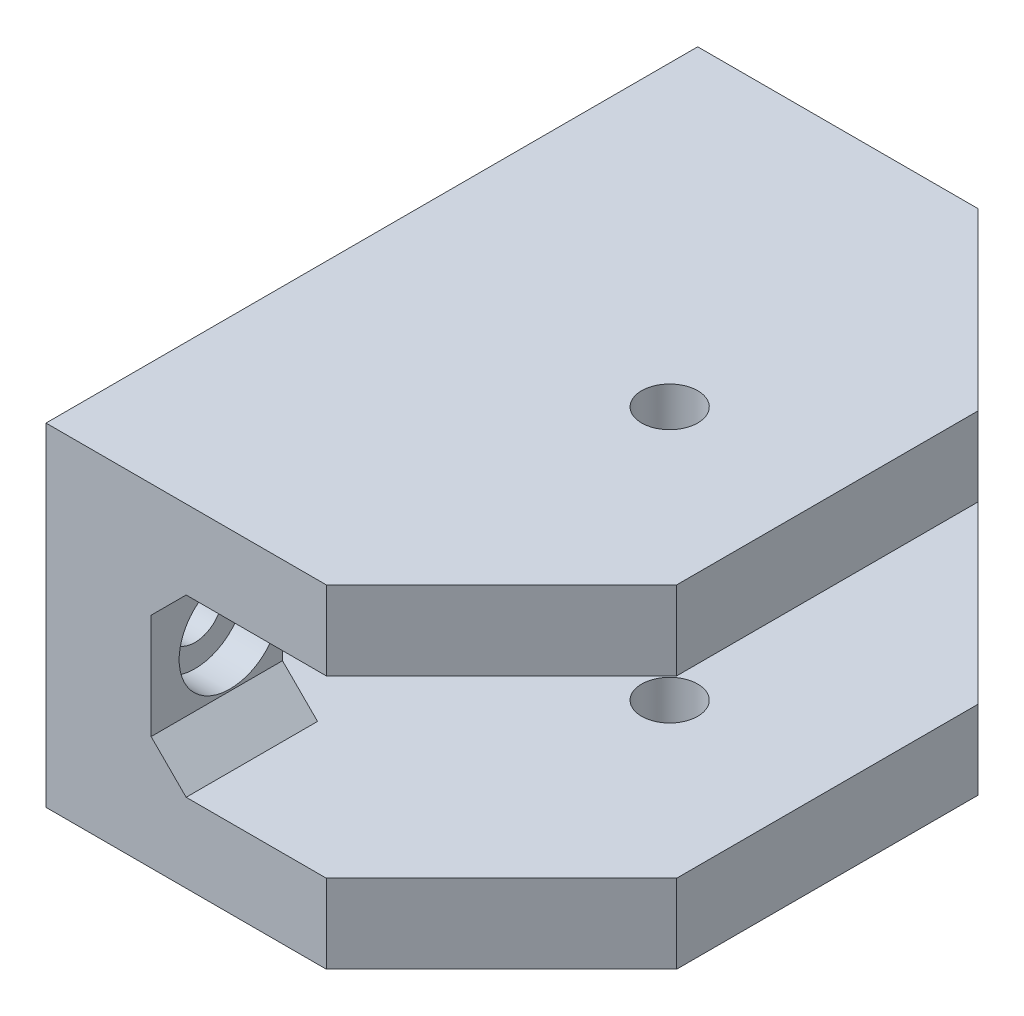
SolidWorks part; units mm, degrees
ref_plane "Front Plane" through (0, 0, 0) normal (0, 0, 1) x (1, 0, 0)
ref_plane "Top Plane" through (0, 0, 0) normal (0, 1, 0) x (1, 0, 0)
ref_plane "Right Plane" through (0, 0, 0) normal (1, 0, 0) x (0, 0, -1)
sketch "Sketch1" plane through (0, 0, 0) normal (0, 1, 0) x (1, 0, 0)
  line L1 (38.6007, -34.5861) -> (64.6007, -34.5861)
  line L2 (38.6007, -34.5861) -> (38.6007, 2.6139)
  line L3 (38.6007, 2.6139) -> (64.6007, 2.6139)
  line L4 (64.6007, -34.5861) -> (64.6007, 2.6139)
  dimension "D1" = 26
  dimension "D2" = 37.2
extrude "Boss-Extrude1" add sketch "Sketch1" along normal blind 19
sketch "Sketch2" plane through (0, 0, 34.5861) normal (0, 0, 1) x (1, 0, 0)
  line L0 (64.6007, 19) -> (64.6007, 0) construction
  line L1 (64.6007, 4.5) -> (44.6007, 4.5)
  line L2 (64.6007, 4.5) -> (64.6007, 14.5)
  line L3 (64.6007, 14.5) -> (44.6007, 14.5)
  line L4 (44.6007, 4.5) -> (44.6007, 14.5)
  line L5 (38.6007, 19) -> (64.6007, 19) construction
  line L6 (38.6007, 0) -> (64.6007, 0) construction
  dimension "D1" = 4.5
  dimension "D2" = 4.5
  dimension "D3" = 20
extrude "Cut-Extrude1" cut sketch "Sketch2" against normal through all
sketch "Sketch3" plane through (0, 0, 0) normal (0, -1, 0) x (1, 0, 0)
  line L0 (64.6007, 34.5861) -> (64.6007, -2.6139) construction
  line L1 (38.6007, 34.5861) -> (64.6007, 34.5861) construction
  circle A0 centre (55.6007, 15.9861) radius 1.6
  dimension "D1" = 3.2
  dimension "D2" = 9
  dimension "D3" = 18.6
extrude "Cut-Extrude2" cut sketch "Sketch3" against normal through all
sketch "Sketch4" plane through (0, 0, 0) normal (0, -1, 0) x (1, 0, 0)
  line L0 (64.6007, 24.5861) -> (54.6007, 34.5861)
  line L1 (64.6007, 34.5861) -> (64.6007, -2.6139) construction
  line L2 (38.6007, 34.5861) -> (64.6007, 34.5861) construction
  line L3 (54.6007, 34.5861) -> (64.6007, 34.5861)
  line L4 (64.6007, 34.5861) -> (64.6007, 24.5861)
  line L5 (64.6007, 7.3861) -> (54.6007, -2.6139)
  line L6 (64.6007, -2.6139) -> (38.6007, -2.6139) construction
  line L7 (54.6007, -2.6139) -> (64.6007, -2.6139)
  line L8 (64.6007, -2.6139) -> (64.6007, 7.3861)
  dimension "D1" = 10
  dimension "D2" = 10
  dimension "D3" = 10
extrude "Cut-Extrude3" cut sketch "Sketch4" against normal through all
sketch "Sketch7" plane through (44.6007, 0, 0) normal (1, 0, 0) x (0, 0, -1)
  line L0 (-7.3861, 4.5) -> (2.6139, 4.5) construction
  line L1 (-4.8861, 4.5) -> (-27.0861, 4.5)
  line L2 (-4.8861, 4.5) -> (-4.8861, 14.5)
  line L3 (-4.8861, 14.5) -> (-27.0861, 14.5)
  line L4 (-27.0861, 4.5) -> (-27.0861, 14.5)
  line L5 (-24.5861, 14.5) -> (-34.5861, 14.5) construction
  line L6 (2.6139, 14.5) -> (2.6139, 4.5) construction
  line L7 (-34.5861, 14.5) -> (-34.5861, 4.5) construction
  dimension "D1" = 7.5
  dimension "D2" = 7.5
extrude "Cut-Extrude6" cut sketch "Sketch7" against normal through all
sketch "Sketch8" plane through (44.6007, 0, 0) normal (1, 0, 0) x (0, 0, -1)
  line L0 (-27.0861, 14.5) -> (-27.0861, 4.5) construction
  line L1 (-4.8861, 4.5) -> (-4.8861, 14.5) construction
  line L2 (2.6139, 14.5) -> (-7.3861, 14.5) construction
  line L3 (-24.5861, 14.5) -> (-34.5861, 14.5) construction
  circle A0 centre (-30.0861, 9.5) radius 1.6
  circle A1 centre (-1.8861, 9.5) radius 1.6
  dimension "D1" = 3.2
  dimension "D2" = 3.2
  dimension "D3" = 3
  dimension "D4" = 3
  dimension "D5" = 5
  dimension "D6" = 5
extrude "Cut-Extrude7" cut sketch "Sketch8" against normal through all
chamfer "Chamfer1" distance 2 angle 45 4 edges at (44.6007, 4.5, 1.1361) (44.6007, 14.5, 1.1361) (44.6007, 14.5, 30.8361) (44.6007, 4.5, 30.8361)
sketch "Sketch9" plane through (44.6007, 0, 0) normal (1, 0, 0) x (0, 0, -1)
  circle A0 centre (-30.0861, 9.5) radius 2.9
  circle A1 centre (-1.8861, 9.5) radius 2.9
  dimension "D1" = 5.8
  dimension "D2" = 5.8
extrude "Cut-Extrude12" cut sketch "Sketch9" against normal blind 2
